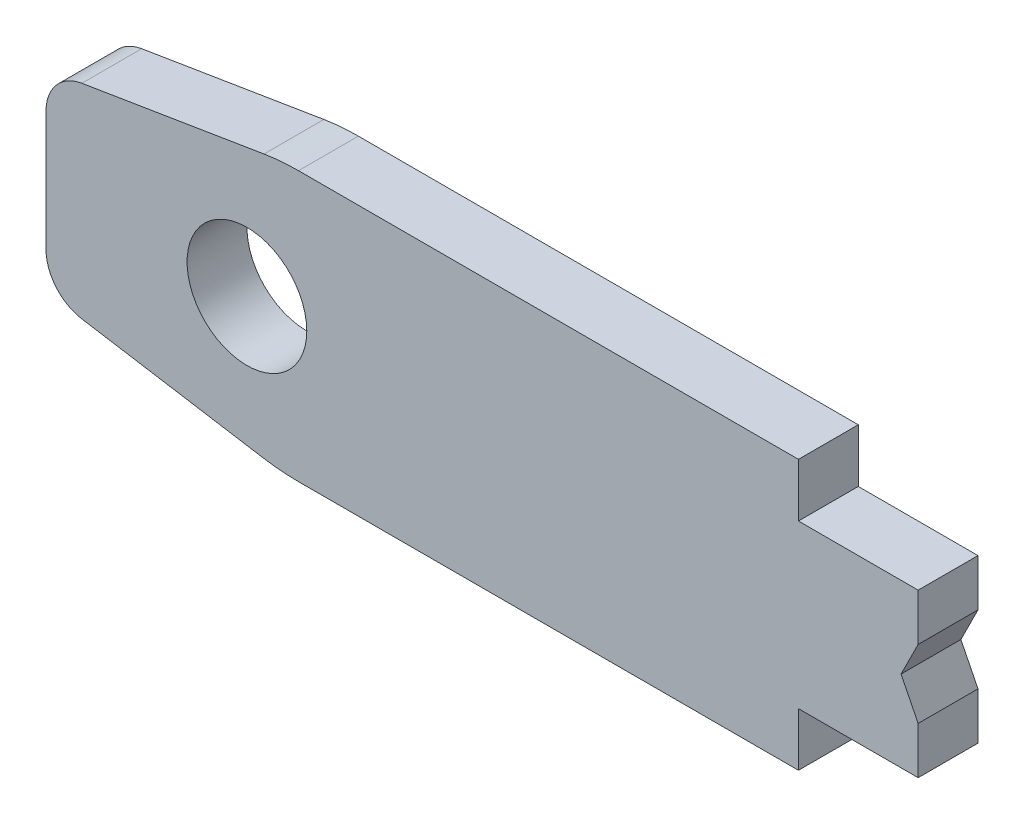
SolidWorks part; units mm, degrees
ref_plane "Plano frontal" through (0, 0, 0) normal (0, 0, 1) x (1, 0, 0)
ref_plane "Plano superior" through (0, 0, 0) normal (0, 1, 0) x (1, 0, 0)
ref_plane "Plano direito" through (0, 0, 0) normal (1, 0, 0) x (0, 0, -1)
sketch "Esboço1" plane through (0, 0, 0) normal (0, 0, 1) x (1, 0, 0)
  line L0 (-5.1011, 3.0844) -> (-9.3615, 2.3872)
  line L1 (-4.2936, -3.15) -> (7.4, -3.15)
  line L2 (-10.2, -1.4003) -> (-10.2, 1.4003)
  line L3 (-4.2936, 3.15) -> (7.4, 3.15)
  line L4 (10.2, -1.9) -> (10.2, -0.8)
  line L5 (-10.2, -3.15) -> (10.2, 3.15) construction
  line L6 (-10.2, 3.15) -> (10.2, -3.15) construction
  line L7 (10.2, 0.8) -> (9.8, 0)
  line L8 (9.8, 0) -> (10.2, -0.8)
  line L9 (7.4, 3.15) -> (7.4, 1.9)
  line L10 (7.4, 1.9) -> (10.2, 1.9)
  line L11 (-9.3615, -2.3872) -> (-5.1011, -3.0844)
  line L12 (10.2, 0.8) -> (10.2, 1.9)
  line L15 (10.2, -1.9) -> (7.4, -1.9)
  line L16 (7.4, -3.15) -> (7.4, -1.9)
  arc A0 (-9.3615, 2.3872) -> (-10.2, 1.4003) centre (-9.2, 1.4003) ccw
  arc A1 (-10.2, -1.4003) -> (-9.3615, -2.3872) centre (-9.2, -1.4003) ccw
  arc A2 (-5.1011, -3.0844) -> (-4.2936, -3.15) centre (-4.2936, 1.85) ccw
  arc A3 (-5.1011, 3.0844) -> (-4.2936, 3.15) centre (-4.2936, -1.85) cw
  circle A4 centre (-5.5, 0) radius 1.4
  point P0 (0, 0)
  point P18 (-4.7, -3.15)
  point P21 (-4.7, 3.15)
  dimension "D7" = 1
  dimension "D8" = 5
  dimension "D3" = 2.8
  dimension "D1" = 6.3
  dimension "D2" = 20.4
  dimension "D4" = 4.7
  dimension "D5" = 2.8
  dimension "D6" = 2.8
  dimension "D9" = 3.8
  dimension "D10" = 1.9
  dimension "D11" = 0.8
  dimension "D12" = 0.8
  dimension "D13" = 0.4
  dimension "D14" = 10.2
extrude "Ressalto-extrusão1" add sketch "Esboço1" along normal blind 1.4
